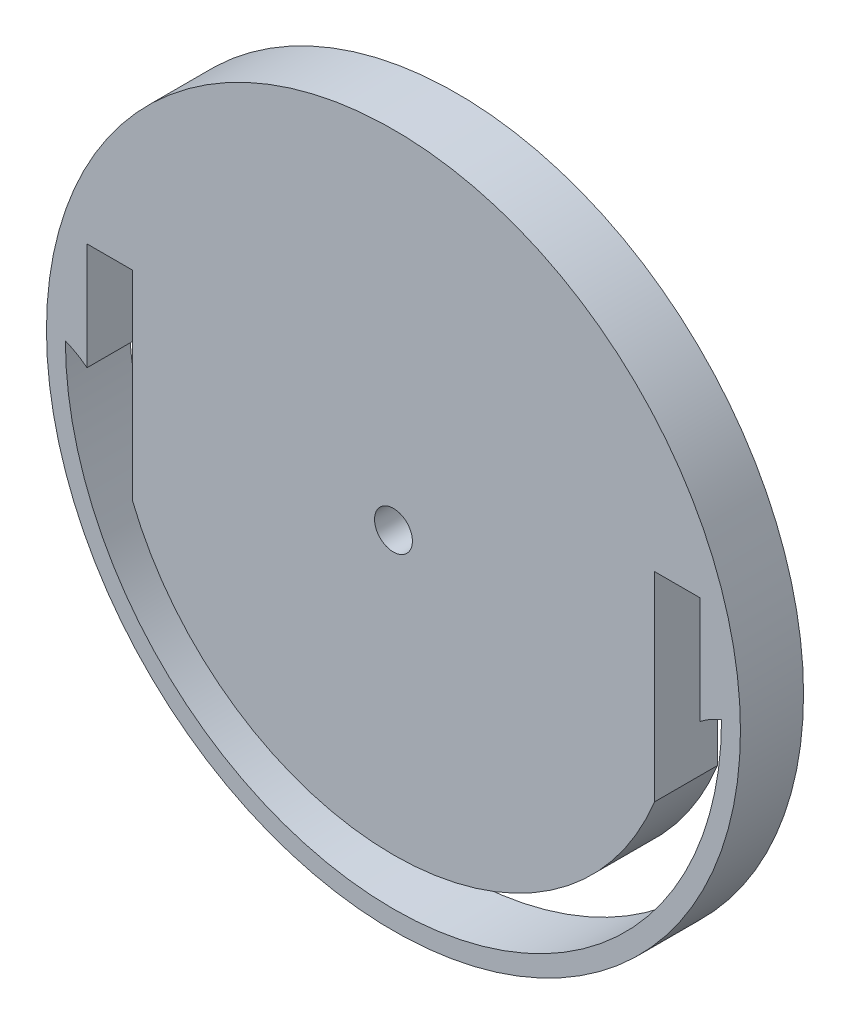
SolidWorks part; units mm, degrees
ref_plane "Front Plane" through (0, 0, 0) normal (0, 0, 1) x (1, 0, 0)
ref_plane "Top Plane" through (0, 0, 0) normal (0, 1, 0) x (1, 0, 0)
ref_plane "Right Plane" through (0, 0, 0) normal (1, 0, 0) x (0, 0, -1)
sketch "Sketch1" plane through (0, 0, 0) normal (0, 0, 1) x (1, 0, 0)
  circle A0 centre (0, 0) radius 55
  circle A1 centre (0, 0) radius 3
extrude "Boss-Extrude1" add sketch "Sketch1" along normal blind 10
sketch "Sketch2" plane through (0, 0, 10) normal (0, 0, 1) x (1, 0, 0)
  line L0 (-55, 0) -> (55, 0) construction
  line L1 (-54.0833, -10) -> (54.0833, -10) construction
  line L2 (-47.962, 14.4195) -> (-41.962, 14.4195) construction
  line L3 (-47.962, 14.4195) -> (-47.962, -6.2527) construction
  line L4 (-48.562, 15.0195) -> (-41.362, 15.0195)
  line L5 (-48.562, 15.0195) -> (-48.562, -1.9737)
  line L7 (-41.362, 15.0195) -> (-41.362, -16.6207)
  line L8 (0, 0) -> (0, 19.7694) construction
  line L9 (41.362, 15.0195) -> (41.362, -16.6207)
  line L10 (48.562, 15.0195) -> (41.362, 15.0195)
  line L11 (48.562, 15.0195) -> (48.562, -1.9737)
  circle A0 centre (0, 0) radius 55 construction
  arc A1 (-52, 0) -> (52, 0) centre (0, 0) ccw
  arc A2 (-41.362, -16.6207) -> (41.362, -16.6207) centre (0, 0) ccw
  arc A3 (-48.562, -1.9737) -> (-52, 0) centre (-57.2847, -13.187) ccw
  arc A4 (48.562, -1.9737) -> (52, 0) centre (57.2847, -13.187) cw
  point P29 (-44.962, 15.0195)
  point P30 (-44.962, 14.4195)
  dimension "D1" = 3
  dimension "D2" = 3
  dimension "D3" = 10
  dimension "D4" = 0.6
  dimension "D5" = 0.6
extrude "Cut-Extrude1" cut sketch "Sketch2" against normal blind 10
